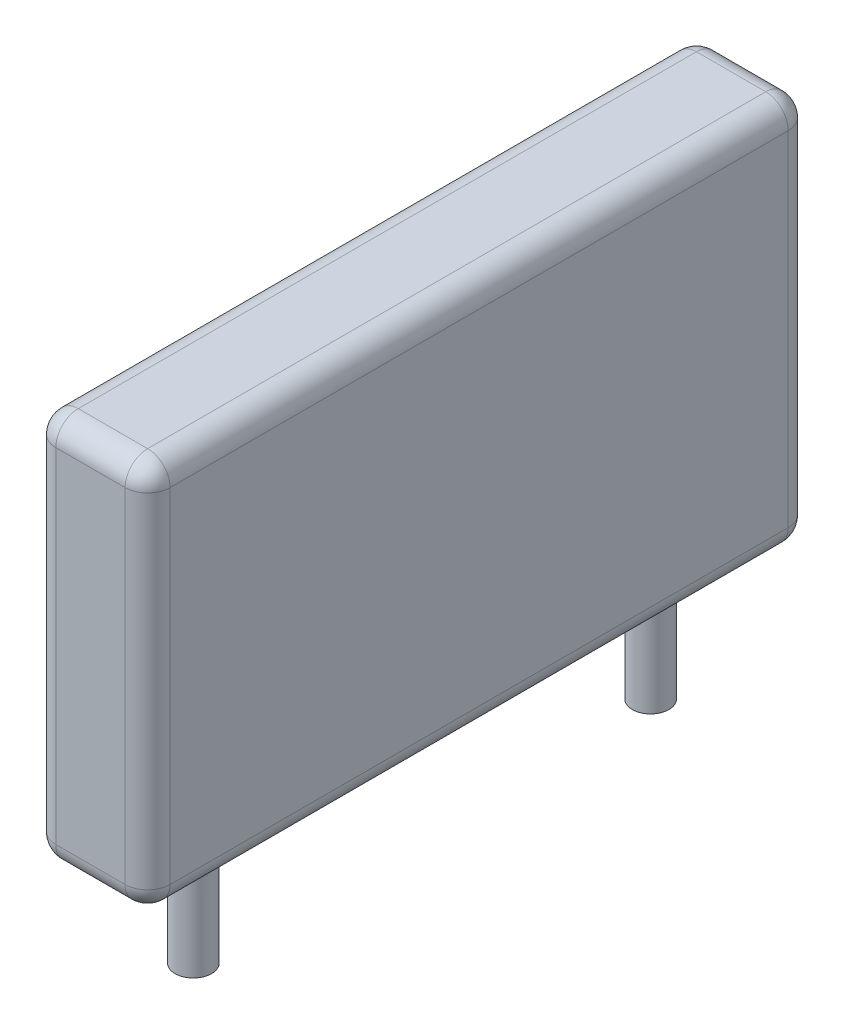
SolidWorks part; units mm, degrees
ref_plane "Front Plane" through (0, 0, 0) normal (0, 0, 1) x (1, 0, 0)
ref_plane "Top Plane" through (0, 0, 0) normal (0, 1, 0) x (1, 0, 0)
ref_plane "Right Plane" through (0, 0, 0) normal (1, 0, 0) x (0, 0, -1)
sketch "Sketch1" plane through (0, 0, 0) normal (1, 0, 0) x (0, 0, -1)
  line L0 (0, 4.318) -> (0, -4.318) construction
  line L1 (-7.366, -4.318) -> (7.366, -4.318)
  line L2 (-7.366, -4.318) -> (-7.366, 4.318)
  line L3 (-7.366, 4.318) -> (7.366, 4.318)
  line L4 (7.366, -4.318) -> (7.366, 4.318)
  line L5 (-7.366, -4.318) -> (7.366, 4.318) construction
  line L6 (-7.366, 4.318) -> (7.366, -4.318) construction
  point P0 (0, 0)
  point P6 (-5.08, -4.318)
  dimension "D1" = 8.636
  dimension "D2" = 14.732
  dimension "D3" = 10.16
extrude "Boss-Extrude1" add sketch "Sketch1" along normal mid plane 2.54
sketch "Sketch2" plane through (0, -4.318, 0) normal (0, -1, 0) x (1, 0, 0)
  circle A0 centre (0, 5.08) radius 0.4064
  dimension "D1" = 0.8128
extrude "Boss-Extrude2" add sketch "Sketch2" along normal blind 2.54
mirror "Mirror1" about plane through (0, 0, 0) normal (0, 0, 1) of "Boss-Extrude2"
fillet "Fillet1" radius 0.5 12 edges at (-1.27, 0, -7.366) (-1.27, 4.318, 0) (-1.27, 0, 7.366) (-1.27, -4.318, 0) (1.27, 0, -7.366) (1.27, 4.318, 0) (1.27, 0, 7.366) (1.27, -4.318, 0) (0, -4.318, -7.366) (0, -4.318, 7.366) (0, 4.318, -7.366) (0, 4.318, 7.366)
